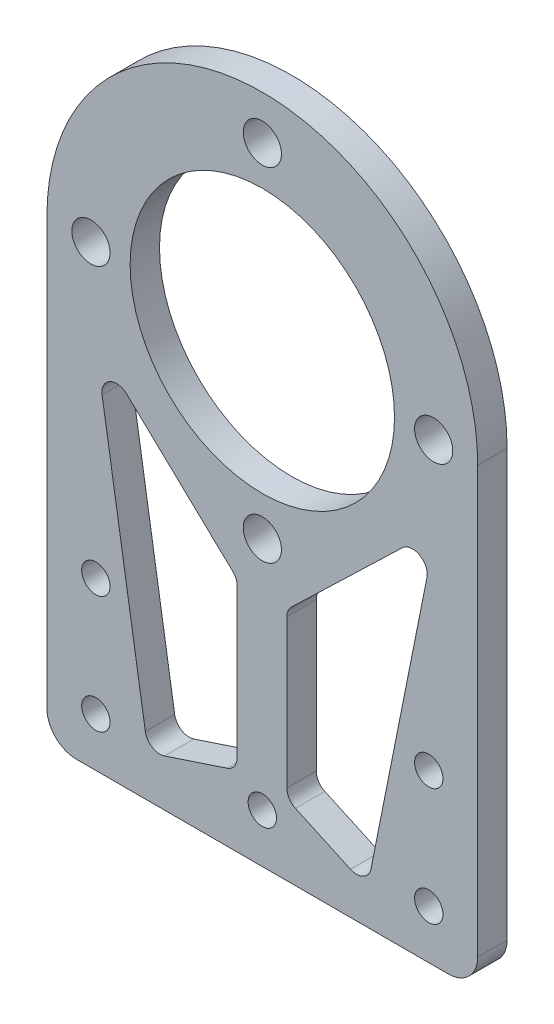
SolidWorks part; units mm, degrees
material "Thornel Mat VMA"
ref_plane "前视基准面" through (0, 0, 0) normal (0, 0, 1) x (1, 0, 0)
ref_plane "上视基准面" through (0, 0, 0) normal (0, 1, 0) x (1, 0, 0)
ref_plane "右视基准面" through (0, 0, 0) normal (1, 0, 0) x (0, 0, -1)
sketch "草图1" plane through (0, 0, 0) normal (0, 0, 1) x (1, 0, 0)
  line L0 (-22, 0) -> (-22, -46.5)
  line L1 (-22, -46.5) -> (22, -46.5)
  line L2 (22, -46.5) -> (22, 0)
  circle A0 centre (0, 0) radius 13.5
  arc A1 (-22, 0) -> (22, 0) centre (0, 0) cw
  circle A2 centre (0, 0) radius 17.5 construction
  circle A3 centre (0, 17.5) radius 1.95
  circle A4 centre (17.5, 0) radius 1.95
  circle A5 centre (-17.5, 0) radius 1.95
  circle A6 centre (0, -17.5) radius 1.95
  dimension "D1" = 27
  dimension "D2" = 35
  dimension "D3" = 3.9
  dimension "D4" = 3.9
  dimension "D5" = 3.9
  dimension "D6" = 3.9
  dimension "D7" = 22
  dimension "D8" = 46.5
extrude "凸台-拉伸1" add sketch "草图1" along normal blind 3
sketch "草图2" plane through (0, 0, 3) normal (0, 0, 1) x (1, 0, 0)
  line L0 (-22, -46.5) -> (22, -46.5) construction
  line L1 (0, -41.5) -> (0, -46.5) construction
  line L2 (-22, 0) -> (-22, -46.5) construction
  line L3 (22, -46.5) -> (22, 0) construction
  circle A0 centre (0, -41.5) radius 1.45
  circle A1 centre (17, -41.5) radius 1.45
  circle A2 centre (-17, -41.5) radius 1.45
  circle A3 centre (-17, -29.5) radius 1.45
  circle A4 centre (17, -29.5) radius 1.45
  dimension "D1" = 2.9
  dimension "D2" = 2.9
  dimension "D3" = 2.9
  dimension "D4" = 5
  dimension "D5" = 5
  dimension "D6" = 5
  dimension "D7" = 17
  dimension "D8" = 17
  dimension "D9" = 5
  dimension "D10" = 5
  dimension "D11" = 2.9
  dimension "D12" = 2.9
  dimension "D13" = 12
  dimension "D14" = 12
extrude "切除-拉伸1" cut sketch "草图2" against normal blind 10
fillet "圆角1" radius 3 2 edges at (-22, -46.5, 1.5) (22, -46.5, 1.5)
sketch "草图3" plane through (0, 0, 3) normal (0, 0, 1) x (1, 0, 0)
  line L0 (17.7526, -7.8275) -> (10.7268, -43.0191)
  line L1 (10.7268, -43.0191) -> (2.5092, -39.2553)
  line L2 (2.5092, -39.2553) -> (2.5092, -22.5026)
  line L3 (2.5092, -22.5026) -> (17.7526, -7.8275)
  line L4 (-17.0626, -8.5803) -> (-2.5719, -22.3214)
  line L5 (-2.5719, -22.3214) -> (-2.5719, -39.2553)
  line L6 (-2.5719, -39.2553) -> (-11.6678, -42.2663)
  line L7 (-11.6678, -42.2663) -> (-17.0626, -8.5803)
  point P6 (-17.0626, -8.5803)
  point P9 (2.6974, -22.3214)
  point P10 (17.7526, -7.8275)
  point P11 (11.6678, -38.628)
  point P12 (-11.9187, -37.7497)
  point P13 (-11.7932, -39.2553)
  point P14 (-11.6678, -42.2663)
  point P15 (10.7268, -43.0191)
  point P16 (2.5092, -39.2553)
extrude "切除-拉伸2" cut sketch "草图3" against normal through all
fillet "圆角2" radius 1.5 8 edges at (-17.0626, -8.5803, 1.5) (-2.5719, -22.3214, 1.5) (-2.5719, -39.2553, 1.5) (-11.6678, -42.2663, 1.5) (17.7526, -7.8275, 1.5) (2.5092, -39.2553, 1.5) (2.5092, -22.5026, 1.5) (10.7268, -43.0191, 1.5)
